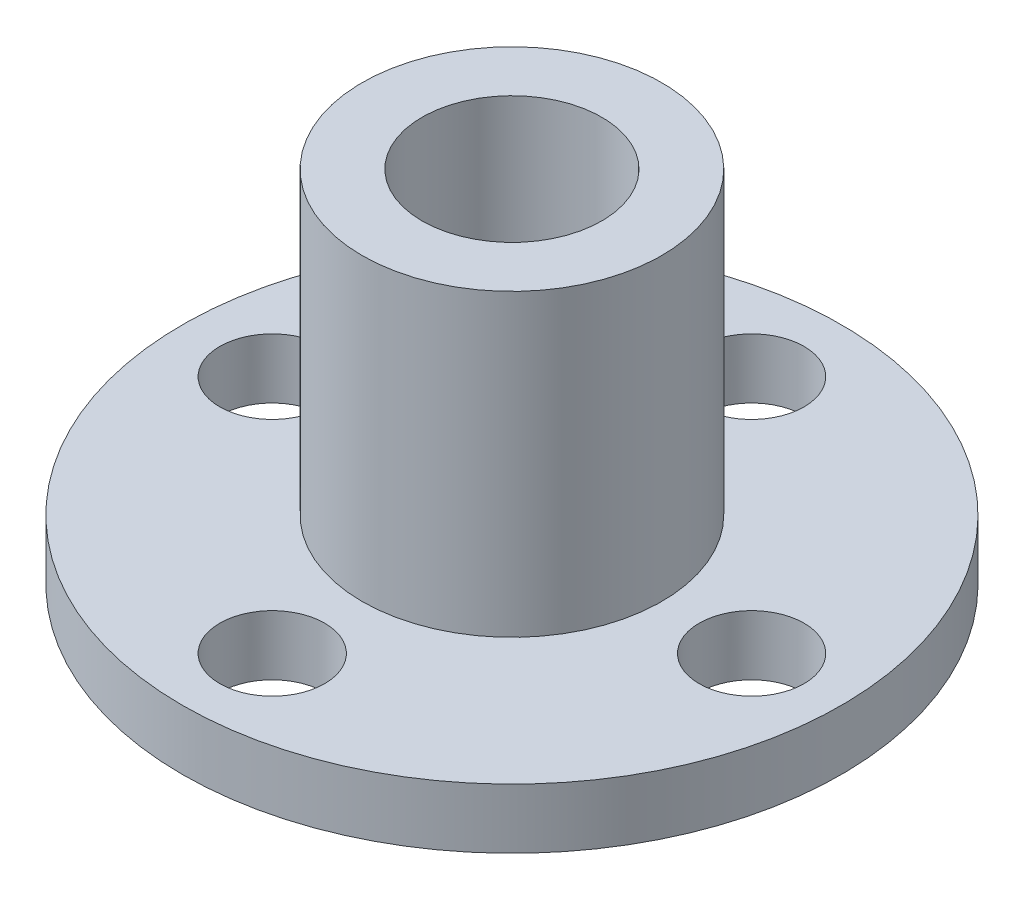
SolidWorks part; units mm, degrees
ref_plane "Alzado" through (0, 0, 0) normal (0, 0, 1) x (1, 0, 0)
ref_plane "Planta" through (0, 0, 0) normal (0, 1, 0) x (1, 0, 0)
ref_plane "Vista lateral" through (0, 0, 0) normal (1, 0, 0) x (0, 0, -1)
sketch "Croquis1" plane through (0, 0, 0) normal (0, 1, 0) x (1, 0, 0)
  circle A0 centre (0, 0) radius 4
  circle A1 centre (0, 0) radius 11
  dimension "D1" = 8
  dimension "D2" = 22
extrude "Saliente-Extruir1" add sketch "Croquis1" along normal blind 2
sketch "Croquis2" plane through (0, 2, 0) normal (0, 1, 0) x (1, 0, 0)
  circle A0 centre (0, 0) radius 5
  circle A1 centre (0, 0) radius 3
  dimension "D1" = 10
  dimension "D2" = 6
extrude "Saliente-Extruir2" add sketch "Croquis2" along normal blind 10
sketch "Croquis3" plane through (0, 0, 0) normal (0, -1, 0) x (1, 0, 0)
  line L0 (-8, 0) -> (8, 0)
  line L1 (0, -8) -> (0, 8)
  circle A0 centre (0, 8) radius 1.75
  circle A1 centre (8, 0) radius 1.75
  circle A2 centre (-8, 0) radius 1.75
  circle A3 centre (0, -8) radius 1.75
  point P5 (0, 0)
  point P9 (0, 0)
  dimension "D3" = 3.5
  dimension "D4" = 3.5
  dimension "D5" = 3.5
  dimension "D6" = 3.5
  dimension "D1" = 16
  dimension "D2" = 16
extrude "Cortar-Extruir1" cut sketch "Croquis3" against normal blind 10
